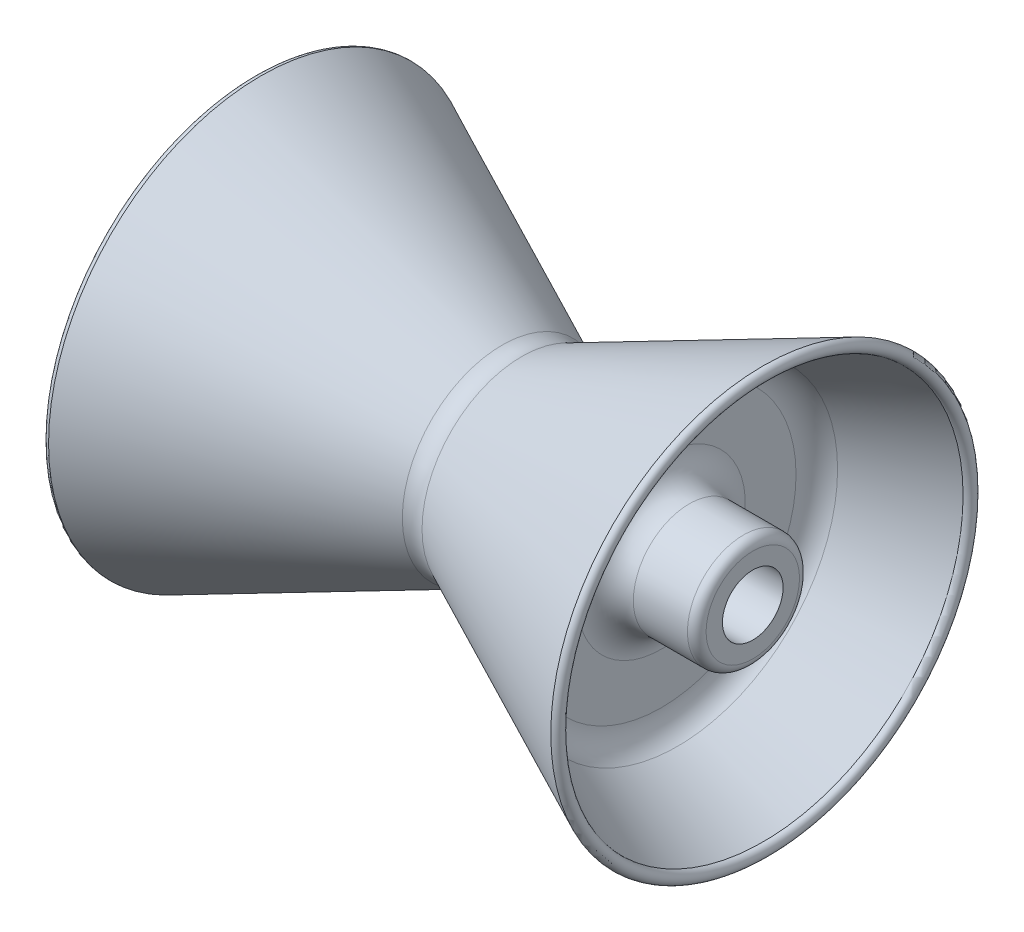
SolidWorks part; units mm, degrees
ref_plane "Front Plane" through (0, 0, 0) normal (0, 0, 1) x (1, 0, 0)
ref_plane "Top Plane" through (0, 0, 0) normal (0, 1, 0) x (1, 0, 0)
ref_plane "Right Plane" through (0, 0, 0) normal (1, 0, 0) x (0, 0, -1)
sketch "Sketch1" plane through (0, 0, 0) normal (0, 0, 1) x (1, 0, 0)
  line L0 (-289.8387, 0) -> (304.3548, 0) construction
  line L1 (0, 85.5904) -> (0, -302.9032) construction
  line L2 (-2.8869, 90.1219) -> (-87.3215, 129.4944)
  line L3 (-130, 102.3051) -> (-130, 32.5)
  line L4 (-130, 32.5) -> (-257.9404, 32.5)
  line L5 (-257.9404, 32.5) -> (-257.9404, 50)
  line L6 (-247.9404, 60) -> (-190, 60)
  line L7 (-160, 90) -> (-160, 144.2728)
  line L8 (-177.3215, 171.4621) -> (-269.015, 214.2195)
  line L9 (269.015, 227.46) -> (10.5655, 106.943)
  line L10 (-269.015, 227.46) -> (-10.5655, 106.943)
  line L11 (177.3215, 171.4621) -> (269.015, 214.2195)
  line L12 (160, 90) -> (160, 144.2728)
  line L13 (247.9404, 60) -> (190, 60)
  line L14 (257.9404, 32.5) -> (257.9404, 50)
  line L15 (130, 32.5) -> (257.9404, 32.5)
  line L16 (130, 102.3051) -> (130, 32.5)
  line L17 (2.8869, 90.1219) -> (87.3215, 129.4944)
  arc A0 (-87.3215, 129.4944) -> (-130, 102.3051) centre (-100, 102.3051) ccw
  arc A1 (-257.9404, 50) -> (-247.9404, 60) centre (-247.9404, 50) cw
  arc A2 (-10.5655, 106.943) -> (10.5655, 106.943) centre (0, 129.6007) ccw
  arc A3 (-190, 60) -> (-160, 90) centre (-190, 90) ccw
  arc A4 (-160, 144.2728) -> (-177.3215, 171.4621) centre (-190, 144.2728) ccw
  arc A5 (-269.015, 227.46) -> (-269.015, 214.2195) centre (-269.015, 220.8397) ccw
  arc A6 (0, 85.5904) -> (-2.8869, 90.1219) centre (-5, 85.5904) ccw
  arc A7 (0, 85.5904) -> (2.8869, 90.1219) centre (5, 85.5904) cw
  arc A8 (269.015, 227.46) -> (269.015, 214.2195) centre (269.015, 220.8397) cw
  arc A9 (160, 144.2728) -> (177.3215, 171.4621) centre (190, 144.2728) cw
  arc A10 (190, 60) -> (160, 90) centre (190, 90) cw
  arc A11 (257.9404, 50) -> (247.9404, 60) centre (247.9404, 50) ccw
  arc A12 (87.3215, 129.4944) -> (130, 102.3051) centre (100, 102.3051) cw
  point P22 (0, 102.0162)
  point P29 (0, 0)
  point P30 (0, 0)
  point P31 (0, 0)
  dimension "D7" = 30
  dimension "D9" = 10
  dimension "D10" = 25
  dimension "D13" = 30
  dimension "D14" = 30
  dimension "D2" = 5
  dimension "D17" = 6.6203
  dimension "D18" = 594.1935
  dimension "D1" = 30
  dimension "D3" = 538.03
  dimension "D4" = 32.5
  dimension "D5" = 60
  dimension "D6" = 227.46
  dimension "D8" = 130
  dimension "D11" = 12
  dimension "D12" = 12
  dimension "D15" = 269.015
  dimension "D16" = 25
  dimension "D19" = 495.8808
revolve "Revolve1" add sketch "Sketch1" angle 360 about L0
